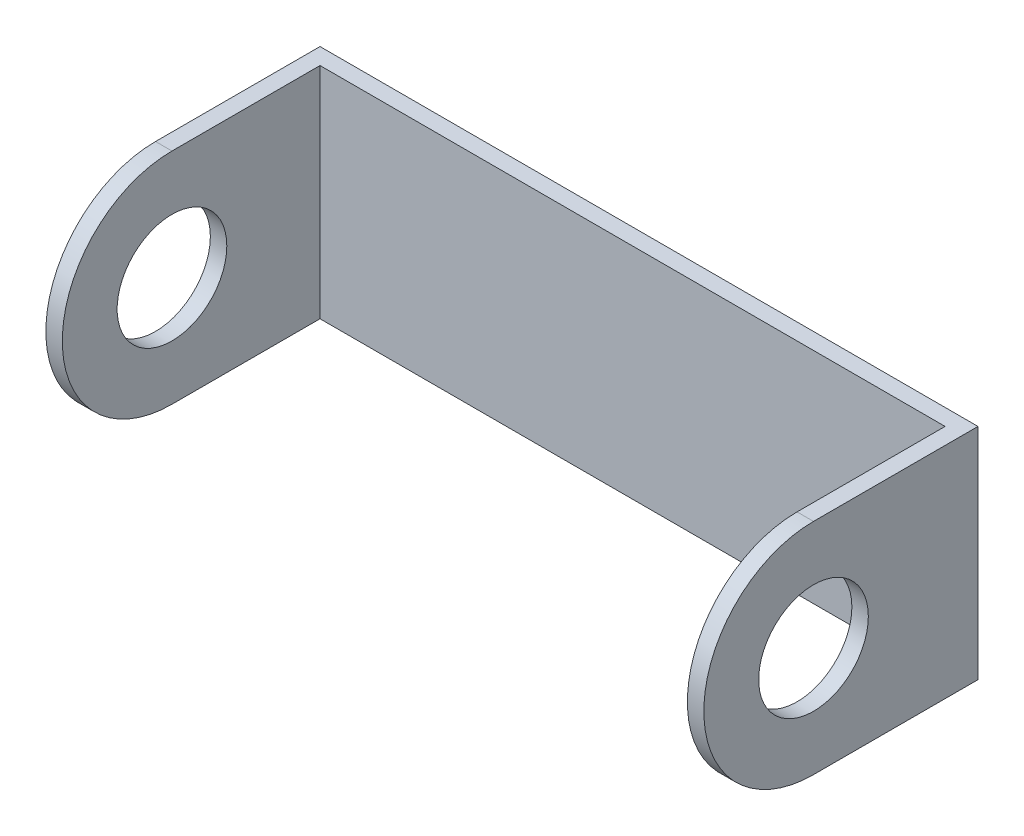
SolidWorks part; units mm, degrees
ref_plane "정면" through (0, 0, 0) normal (0, 0, 1) x (1, 0, 0)
ref_plane "윗면" through (0, 0, 0) normal (0, 1, 0) x (1, 0, 0)
ref_plane "우측면" through (0, 0, 0) normal (1, 0, 0) x (0, 0, -1)
sketch "스케치1" plane through (0, 0, 0) normal (1, 0, 0) x (0, 0, -1)
  line L0 (0, -20) -> (0, 20)
  line L1 (0, 20) -> (-3, 20)
  line L2 (-3, 20) -> (-3, -20)
  line L3 (-3, -20) -> (0, -20)
  point P5 (0, 0)
  dimension "D1" = 3
  dimension "D2" = 40
extrude "보스-돌출1" add sketch "스케치1" along normal mid plane 114
sketch "스케치2" plane through (57, 0, 0) normal (1, 0, 0) x (0, 0, -1)
  line L0 (0, 20) -> (-30, 20)
  line L1 (0, -20) -> (-30, -20)
  line L2 (0, 20) -> (0, -20)
  arc A0 (-30, 20) -> (-30, -20) centre (-30, 0) ccw
  circle A1 centre (-30, 0) radius 10
  dimension "D1" = 40
  dimension "D3" = 20
  dimension "D2" = 30
extrude "보스-돌출2" add sketch "스케치2" along normal blind 3
mirror "대칭 복사1" about plane through (0, 0, 0) normal (1, 0, 0) of "보스-돌출2"
